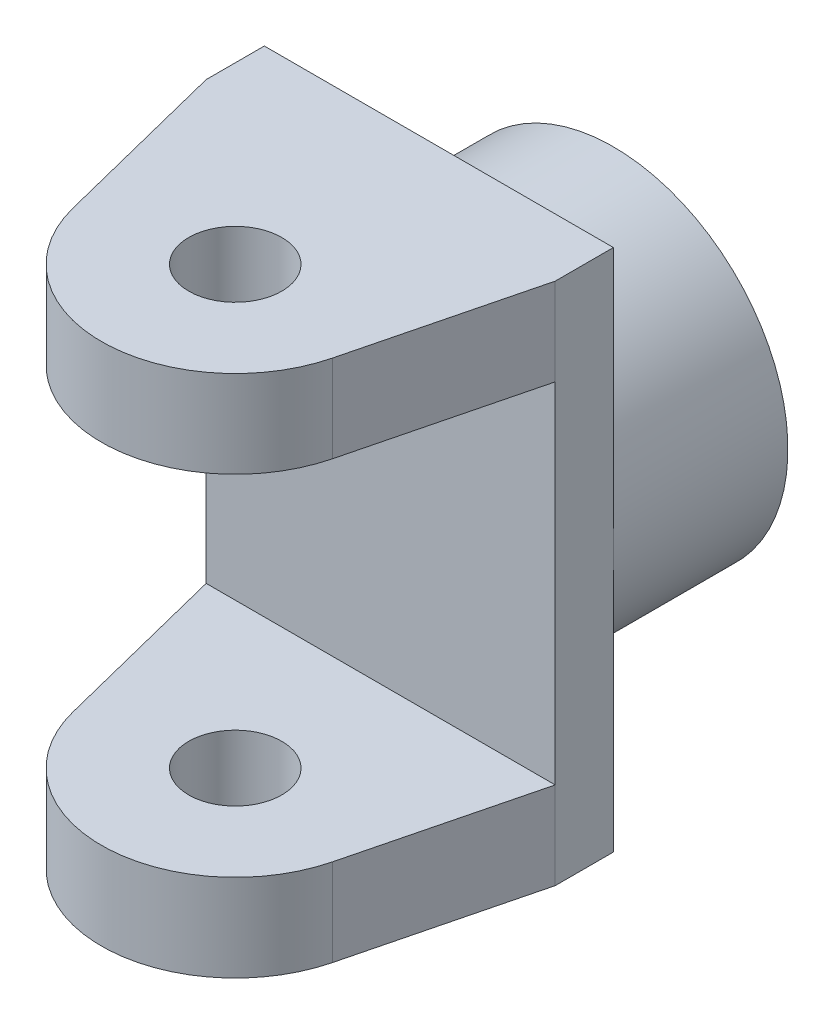
SolidWorks part; units mm, degrees
ref_plane "Front Plane" through (0, 0, 0) normal (0, 0, 1) x (1, 0, 0)
ref_plane "Top Plane" through (0, 0, 0) normal (0, 1, 0) x (1, 0, 0)
ref_plane "Right Plane" through (0, 0, 0) normal (1, 0, 0) x (0, 0, -1)
sketch "Sketch1" plane through (0, 0, 0) normal (0, 0, 1) x (1, 0, 0)
  line L1 (-30, -45) -> (30, -45)
  line L2 (-30, -45) -> (-30, 45)
  line L3 (-30, 45) -> (30, 45)
  line L4 (30, -45) -> (30, 45)
  line L5 (-30, -45) -> (30, 45) construction
  line L6 (-30, 45) -> (30, -45) construction
  point P0 (0, 0)
  dimension "D1" = 60
  dimension "D2" = 90
extrude "Boss-Extrude1" add sketch "Sketch1" along normal blind 10
sketch "Sketch2" plane through (0, 0, 0) normal (0, 0, -1) x (-1, 0, 0)
  line L0 (4, -13.9127) -> (4, -13.3253)
  line L3 (-4, -16.9127) -> (4, -16.9127)
  line L4 (4, -13.9127) -> (4, -16.9127)
  line L5 (-4, -13.9127) -> (-4, -13.3253)
  line L6 (-4, -13.9127) -> (-4, -16.9127)
  circle A0 centre (0, 0) radius 30
  arc A1 (4, -13.3253) -> (-4, -13.3253) centre (0, 0) ccw
  dimension "D1" = 60
  dimension "D2" = 3
extrude "Boss-Extrude2" add sketch "Sketch2" along normal blind 30
sketch "Sketch6" plane through (0, 45, 0) normal (0, 1, 0) x (1, 0, 0)
  line L0 (-30, -10) -> (-22.306, -40.6072)
  line L1 (30, 0) -> (-30, 0) construction
  line L2 (30, -10) -> (-30, -10)
  line L3 (30, -10) -> (22.306, -40.6072)
  circle A0 centre (0, -35) radius 8
  arc A1 (-22.306, -40.6072) -> (22.306, -40.6072) centre (0, -35) ccw
  dimension "D1" = 16
  dimension "D2" = 35
extrude "Boss-Extrude3" add sketch "Sketch6" against normal blind 15
mirror "Mirror1" about plane through (0, 0, 0) normal (0, 1, 0) of "Boss-Extrude3"
